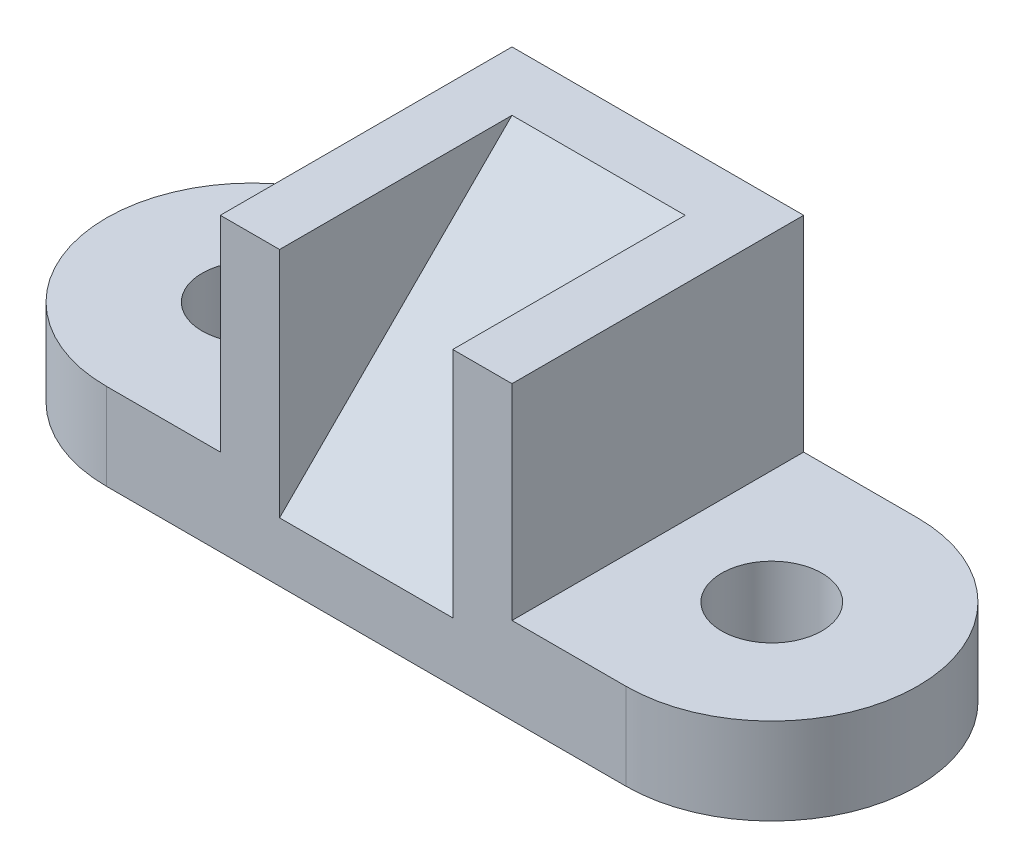
SolidWorks part; units mm, degrees
ref_plane "Front Plane" through (0, 0, 0) normal (0, 0, 1) x (1, 0, 0)
ref_plane "Top Plane" through (0, 0, 0) normal (0, 1, 0) x (1, 0, 0)
ref_plane "Right Plane" through (0, 0, 0) normal (1, 0, 0) x (0, 0, -1)
sketch "Sketch1" plane through (0, 0, 0) normal (0, 1, 0) x (1, 0, 0)
  line L0 (-57, 0) -> (57, 0) construction
  line L2 (-57, 32) -> (57, 32)
  line L3 (-57, -32) -> (57, -32)
  arc A0 (-57, 32) -> (-57, -32) centre (-57, 0) ccw
  arc A1 (57, -32) -> (57, 32) centre (57, 0) ccw
  circle A2 centre (57, 0) radius 11
  circle A3 centre (-57, 0) radius 11
  point P5 (0, 0)
  dimension "D2" = 32
  dimension "D3" = 22
  dimension "D4" = 22
  dimension "D1" = 114
extrude "Boss-Extrude1" add sketch "Sketch1" along normal blind 19
sketch "Sketch2" plane through (0, 19, 0) normal (0, 1, 0) x (1, 0, 0)
  line L1 (-32, 32) -> (32, 32)
  line L2 (-32, 32) -> (-32, -32)
  line L3 (-32, -32) -> (32, -32)
  line L4 (32, 32) -> (32, -32)
  line L5 (-32, 32) -> (32, -32) construction
  line L6 (-32, -32) -> (32, 32) construction
  point P0 (0, 0)
  dimension "D1" = 64
extrude "Boss-Extrude2" add sketch "Sketch2" along normal blind 45
sketch "Sketch3" plane through (-32, 0, 0) normal (-1, 0, 0) x (0, 0, 1)
  line L0 (32, 64) -> (-19, 64)
  line L1 (-32, 64) -> (32, 64) construction
  line L2 (-19, 64) -> (32, 13)
  line L3 (32, 19) -> (32, 0) construction
  line L4 (32, 13) -> (32, 64)
  dimension "D1" = 13
  dimension "D2" = 13
extrude "Cut-Extrude1" cut sketch "Sketch3" against normal blind 38 from offset 13
